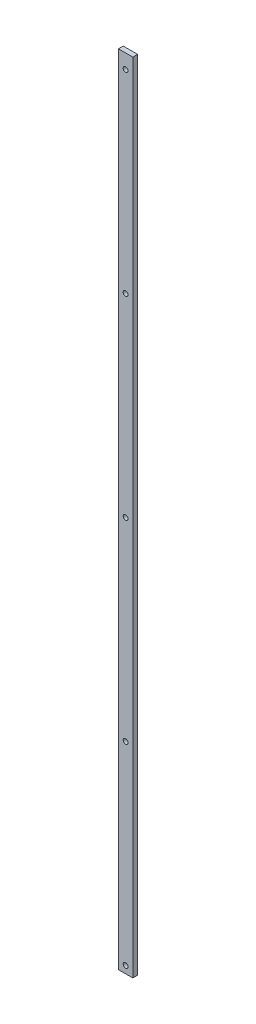
SolidWorks part; units mm, degrees
ref_plane "Front Plane" through (0, 0, 0) normal (0, 0, 1) x (1, 0, 0)
ref_plane "Top Plane" through (0, 0, 0) normal (0, 1, 0) x (1, 0, 0)
ref_plane "Right Plane" through (0, 0, 0) normal (1, 0, 0) x (0, 0, -1)
sketch "Sketch1" plane through (0, 0, 0) normal (0, 0, 1) x (1, 0, 0)
  line L0 (9.525, 0) -> (9.525, 1054.735) construction
  line L1 (0, 0) -> (19.05, 0)
  line L2 (0, 0) -> (0, 1054.735)
  line L3 (0, 1054.735) -> (19.05, 1054.735)
  line L4 (19.05, 0) -> (19.05, 1054.735)
  circle A0 centre (9.525, 9.525) radius 3.175
  circle A1 centre (9.525, 266.065) radius 3.175
  circle A2 centre (9.525, 522.605) radius 3.175
  circle A3 centre (9.525, 779.145) radius 3.175
  circle A4 centre (9.525, 1035.685) radius 3.175
  dimension "D5" = 6.35
  dimension "D2" = 19.05
  dimension "D1" = 19.05
  dimension "D3" = 9.525
  dimension "D4" = 5
extrude "Boss-Extrude1" add sketch "Sketch1" along normal blind 6.35
